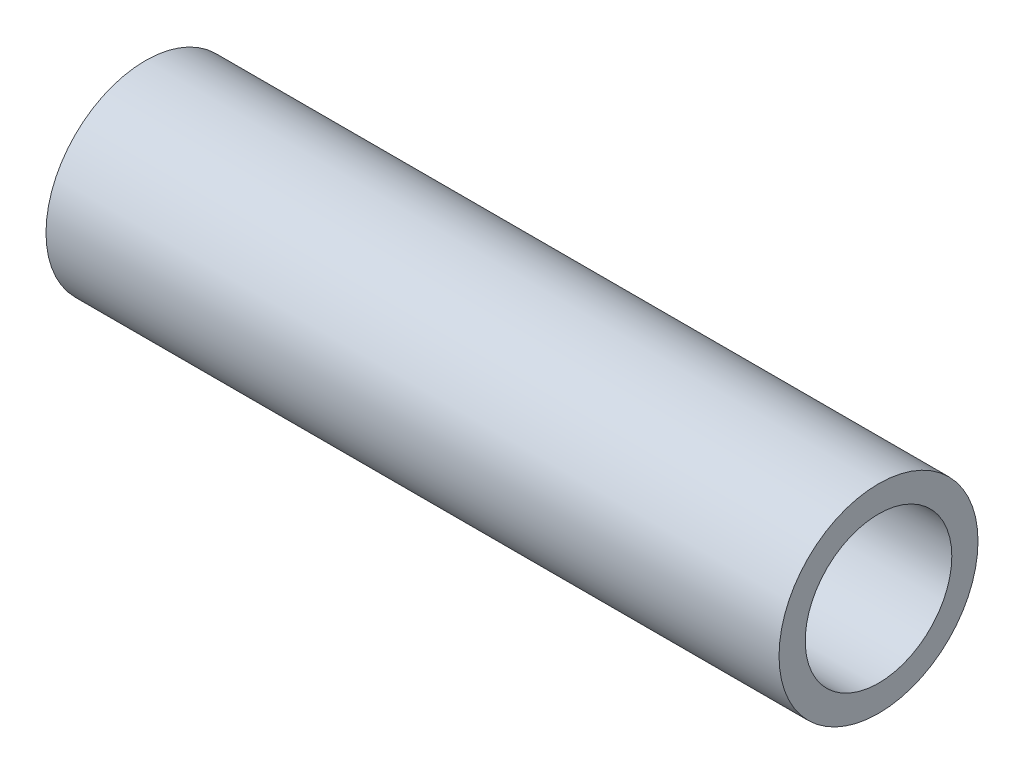
SolidWorks part; units mm, degrees
ref_plane "Front Plane" through (0, 0, 0) normal (0, 0, 1) x (1, 0, 0)
ref_plane "Top Plane" through (0, 0, 0) normal (0, 1, 0) x (1, 0, 0)
ref_plane "Right Plane" through (0, 0, 0) normal (1, 0, 0) x (0, 0, -1)
sketch "Sketch1" plane through (0, 0, 0) normal (1, 0, 0) x (0, 0, -1)
  circle A0 centre (0, 0) radius 7.112
  circle A1 centre (0, 0) radius 9.652
  dimension "D1" = 14.224
  dimension "D2" = 2.54
extrude "Boss-Extrude1" add sketch "Sketch1" along normal blind 71.12
